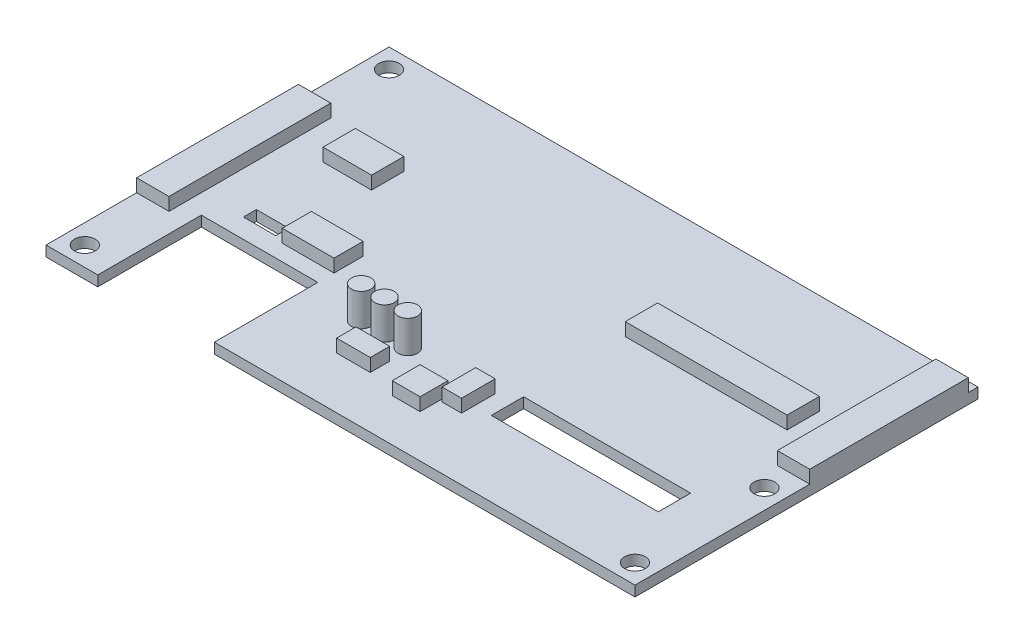
SolidWorks part; units mm, degrees
ref_plane "前视基准面" through (0, 0, 0) normal (0, 0, 1) x (1, 0, 0)
ref_plane "上视基准面" through (0, 0, 0) normal (0, 1, 0) x (1, 0, 0)
ref_plane "右视基准面" through (0, 0, 0) normal (1, 0, 0) x (0, 0, -1)
sketch "草图2" plane through (0, 0, 0) normal (0, 1, 0) x (1, 0, 0)
  line L0 (0, 0) -> (0, -53)
  line L1 (0, 0) -> (91, 0) construction
  line L2 (0, 0) -> (0, -53) construction
  line L3 (0, -53) -> (91, -53) construction
  line L4 (91, 0) -> (91, -53) construction
  line L5 (8, -53) -> (26, -53) construction
  line L6 (8, -53) -> (8, -37) construction
  line L7 (8, -37) -> (26, -37) construction
  line L8 (26, -53) -> (26, -37) construction
  line L9 (0, -53) -> (8, -53)
  line L10 (8, -53) -> (8, -37)
  line L11 (8, -37) -> (26, -37)
  line L12 (26, -37) -> (26, -53)
  line L13 (26, -53) -> (91, -53)
  line L14 (91, -53) -> (91, 0)
  line L15 (91, 0) -> (0, 0)
  line L17 (11.5, -34) -> (16.5, -34)
  line L18 (11.5, -34) -> (11.5, -32)
  line L19 (11.5, -32) -> (16.5, -32)
  line L20 (16.5, -34) -> (16.5, -32)
  line L21 (83, -41.4) -> (57.2, -41.4)
  line L22 (83, -41.4) -> (83, -36.4)
  line L23 (83, -36.4) -> (57.2, -36.4)
  line L24 (57.2, -41.4) -> (57.2, -36.4)
  circle A0 centre (3, -50) radius 1.6
  circle A1 centre (3, -3) radius 1.6
  circle A2 centre (88, -30) radius 1.6
  circle A3 centre (88, -50) radius 1.6
  dimension "D14" = 3.2
  dimension "D15" = 3.2
  dimension "D16" = 3.2
  dimension "D17" = 3.2
  dimension "D1" = 91
  dimension "D2" = 53
  dimension "D3" = 8
  dimension "D4" = 18
  dimension "D5" = 16
  dimension "D6" = 11.5
  dimension "D7" = 19
  dimension "D8" = 5
  dimension "D9" = 2
  dimension "D10" = 8
  dimension "D11" = 11.6
  dimension "D12" = 25.8
  dimension "D13" = 5
  dimension "D18" = 3
  dimension "D19" = 3
  dimension "D20" = 3
  dimension "D21" = 3
  dimension "D22" = 3
  dimension "D23" = 3
  dimension "D24" = 3
  dimension "D25" = 23
extrude "凸台-拉伸1" add sketch "草图2" along normal blind 1.6
sketch "草图3" plane through (0, 1.6, 0) normal (0, 1, 0) x (1, 0, 0)
  line L0 (0, 0) -> (0, -53) construction
  line L1 (5, -14) -> (0, -14)
  line L2 (5, -14) -> (5, -39)
  line L3 (5, -39) -> (0, -39)
  line L4 (0, -14) -> (0, -39)
  line L5 (91, 0) -> (0, 0) construction
  line L6 (10.3, -15.5) -> (17.8, -15.5)
  line L7 (10.3, -15.5) -> (10.3, -20.5)
  line L8 (10.3, -20.5) -> (17.8, -20.5)
  line L9 (17.8, -15.5) -> (17.8, -20.5)
  line L10 (18, -34.5) -> (26, -34.5)
  line L11 (18, -34.5) -> (18, -30)
  line L12 (18, -30) -> (26, -30)
  line L13 (26, -34.5) -> (26, -30)
  line L14 (57, -20.5) -> (82, -20.5)
  line L15 (57, -20.5) -> (57, -15.5)
  line L16 (57, -15.5) -> (82, -15.5)
  line L17 (82, -20.5) -> (82, -15.5)
  line L22 (91, -53) -> (91, 0) construction
  line L24 (91, -1.5) -> (86, -1.5)
  line L25 (91, -1.5) -> (91, -26)
  line L26 (91, -26) -> (86, -26)
  line L27 (86, -1.5) -> (86, -26)
  dimension "D1" = 14
  dimension "D2" = 25
  dimension "D3" = 5
  dimension "D4" = 15.5
  dimension "D5" = 10.3
  dimension "D6" = 5
  dimension "D7" = 7.5
  dimension "D8" = 30
  dimension "D9" = 18
  dimension "D10" = 8
  dimension "D11" = 4.5
  dimension "D12" = 15.5
  dimension "D13" = 9
  dimension "D14" = 25
  dimension "D15" = 5
  dimension "D16" = 1.5
  dimension "D17" = 24.5
  dimension "D18" = 5
extrude "凸台-拉伸2" add sketch "草图3" along normal blind 2
sketch "草图4" plane through (0, 1.6, 0) normal (0, 1, 0) x (1, 0, 0)
  line L0 (0, -38.8) -> (51.129, -38.8) construction
  line L1 (0, -39) -> (0, -53) construction
  line L2 (0, -53) -> (8, -53) construction
  circle A0 centre (34.5, -38.8) radius 1.5
  circle A1 centre (38.1, -38.8) radius 1.5
  circle A2 centre (41.7, -38.8) radius 1.5
  dimension "D1" = 3
  dimension "D2" = 3
  dimension "D7" = 3
  dimension "D3" = 14.2
  dimension "D4" = 34.5
  dimension "D5" = 3.6
  dimension "D6" = 3.6
extrude "凸台-拉伸3" add sketch "草图4" along normal blind 5
sketch "草图5" plane through (0, 1.6, 0) normal (0, 1, 0) x (1, 0, 0)
  line L0 (26, -53) -> (91, -53) construction
  line L1 (36.9, -42) -> (42.1, -42)
  line L2 (36.9, -42) -> (36.9, -45)
  line L3 (36.9, -45) -> (42.1, -45)
  line L4 (42.1, -42) -> (42.1, -45)
  line L5 (46.9, -42.1) -> (51.2, -42.1)
  line L6 (46.9, -42.1) -> (46.9, -46.4)
  line L7 (46.9, -46.4) -> (51.2, -46.4)
  line L8 (51.2, -42.1) -> (51.2, -46.4)
  line L9 (51.6, -38.2) -> (54.6, -38.2)
  line L10 (51.6, -38.2) -> (51.6, -43.4)
  line L11 (51.6, -43.4) -> (54.6, -43.4)
  line L12 (54.6, -38.2) -> (54.6, -43.4)
  line L13 (0, -39) -> (0, -53) construction
  dimension "D1" = 5.2
  dimension "D2" = 3
  dimension "D3" = 5.2
  dimension "D4" = 3
  dimension "D5" = 8
  dimension "D6" = 36.9
  dimension "D7" = 46.9
  dimension "D8" = 6.6
  dimension "D9" = 4.3
  dimension "D10" = 4.3
  dimension "D11" = 9.6
  dimension "D12" = 51.6
extrude "凸台-拉伸4" add sketch "草图5" along normal blind 2
